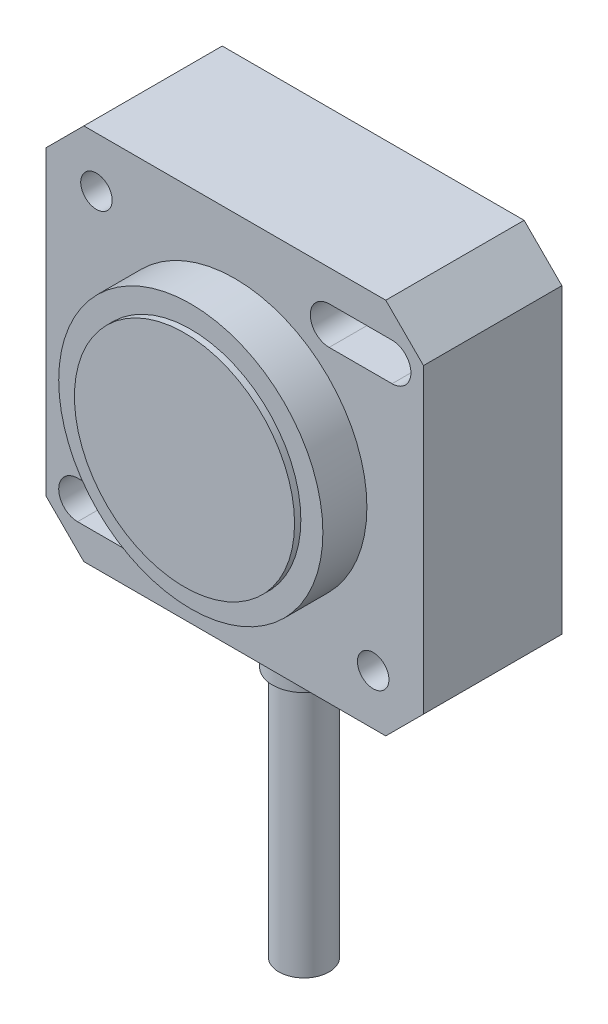
SolidWorks part; units mm, degrees
ref_plane "Face" through (0, 0, 0) normal (0, 0, 1) x (1, 0, 0)
ref_plane "Dessus" through (0, 0, 0) normal (0, 1, 0) x (1, 0, 0)
ref_plane "Droite" through (0, 0, 0) normal (1, 0, 0) x (0, 0, -1)
sketch "Esquisse1" plane through (0, 0, 0) normal (0, 0, 1) x (1, 0, 0)
  line L1 (-15, 15) -> (15, 15)
  line L2 (-15, 15) -> (-15, -15)
  line L3 (-15, -15) -> (15, -15)
  line L4 (15, 15) -> (15, -15)
  dimension "D1" = 15
  dimension "D2" = 30
  dimension "D3" = 15
  dimension "D4" = 30
extrude "Boss.-Extru.1" add sketch "Esquisse1" along normal blind 11
hole_wizard "Trou taraudé M31" positions "Esquisse4" profile "Esquisse3" tap size "M3" standard "Iso" end condition up to next
sketch "Esquisse4" plane through (0, 0, 11) normal (0, 0, 1) x (1, 0, 0)
  point P0 (11, -11)
  point P3 (-11, 11)
cosmetic thread "Filetage de perçage1" parameters "D2"=3
cosmetic thread "Filetage de perçage2" parameters "D2"=3
sketch "Esquisse3" plane through (11, -11, 11) normal (1, 0, 0) x (0, -1, 0)
  line L0 (0, 0) -> (0, 11)
  line L1 (0, 11) -> (1.25, 11)
  line L2 (1.25, 11) -> (1.25, 0)
  line L5 (1.25, 0) -> (0, 0)
  line L11 (0, -6.35) -> (0, 107.95) construction
  dimension "Diamètre du trou pour taraudage jusqu'au prochain" = 2.5
  dimension "Profondeur du trou pour taraudage jusqu'au prochain" = 11
sketch "Esquisse5" plane through (0, 0, 11) normal (0, 0, 1) x (1, 0, 0)
  line L0 (12.5, 12.5) -> (7.5, 12.5)
  line L1 (12.5, 9.5) -> (7.5, 9.5)
  line L2 (-7.5, -9.5) -> (-12.5, -9.5)
  line L3 (-7.5, -12.5) -> (-12.5, -12.5)
  arc A0 (12.5, 9.5) -> (12.5, 12.5) centre (12.5, 11) ccw
  arc A1 (7.5, 12.5) -> (7.5, 9.5) centre (7.5, 11) ccw
  arc A2 (-7.5, -12.5) -> (-7.5, -9.5) centre (-7.5, -11) ccw
  arc A3 (-12.5, -9.5) -> (-12.5, -12.5) centre (-12.5, -11) ccw
  dimension "D1" = 11
  dimension "D3" = 5
  dimension "D2" = 12.5
  dimension "D4" = 12.5
  dimension "D5" = 5
extrude "Enlèv. mat.-Extru.1" cut sketch "Esquisse5" against normal up to next
sketch "Esquisse6" plane through (0, 0, 11) normal (0, 0, 1) x (1, 0, 0)
  circle A0 centre (0, 0) radius 10.5
extrude "Boss.-Extru.2" add sketch "Esquisse6" along normal blind 3.5
sketch "Esquisse7" plane through (0, 0, 14.5) normal (0, 0, 1) x (1, 0, 0)
  circle A0 centre (0, 0) radius 8.75
extrude "Boss.-Extru.3" add sketch "Esquisse7" along normal blind 0.5
sketch "Esquisse8" plane through (0, -15, 0) normal (0, -1, 0) x (-1, 0, 0)
  circle A0 centre (0, -5.5) radius 2.5
extrude "Boss.-Extru.4" add sketch "Esquisse8" along normal blind 4
sketch "Esquisse9" plane through (0, -19, 0) normal (0, -1, 0) x (-1, 0, 0)
  circle A0 centre (0, -5.5) radius 2
extrude "Boss.-Extru.5" add sketch "Esquisse9" along normal blind 20
chamfer "Chanfrein1" distance 3 angle 45 4 edges at (-15, -15, 5.5) (-15, 15, 5.5) (15, -15, 5.5) (15, 15, 5.5)
sketch "Esquisse10" plane through (0, 0, 0) normal (0, 0, -1) x (-1, 0, 0)
  line L0 (-7.5, 8) -> (-12.5, 8)
  line L1 (7.5, -8) -> (12.5, -8)
  line L2 (-10.9645, -7.9645) -> (-12.5, -7.9645)
  line L3 (-7.9645, -10.9645) -> (-7.9645, -12.5)
  line L4 (-12.5, -7.9645) -> (-12.5, 8)
  line L5 (-4.5, 11) -> (-4.5, 12.5)
  line L6 (4.5, -11) -> (4.5, -12.5)
  line L8 (11, 8) -> (12.5, 8)
  line L10 (12.5, 8) -> (12.5, -8)
  line L12 (4.5, -12.5) -> (-7.9645, -12.5)
  line L13 (-4.5, 12.5) -> (8, 12.5)
  line L14 (8, 11) -> (8, 12.5)
  arc A0 (-7.5, 8) -> (-4.5, 11) centre (-7.5, 11) ccw
  arc A1 (8, 11) -> (11, 8) centre (11, 11) ccw
  arc A2 (-7.9645, -10.9645) -> (-10.9645, -7.9645) centre (-10.9645, -10.9645) ccw
  arc A3 (7.5, -8) -> (4.5, -11) centre (7.5, -11) ccw
  point P6 (-10.9645, 12.5)
  point P17 (10.9645, 12.5)
  point P18 (12.5, 10.9645)
  point P19 (12.5, -10.9645)
  point P20 (10.9645, -12.5)
  point P21 (-10.9645, -12.5)
  point P22 (-12.5, -10.9645)
  point P23 (-12.5, 10.9645)
extrude "Enlèv. mat.-Extru.2" cut sketch "Esquisse10" against normal blind 3
